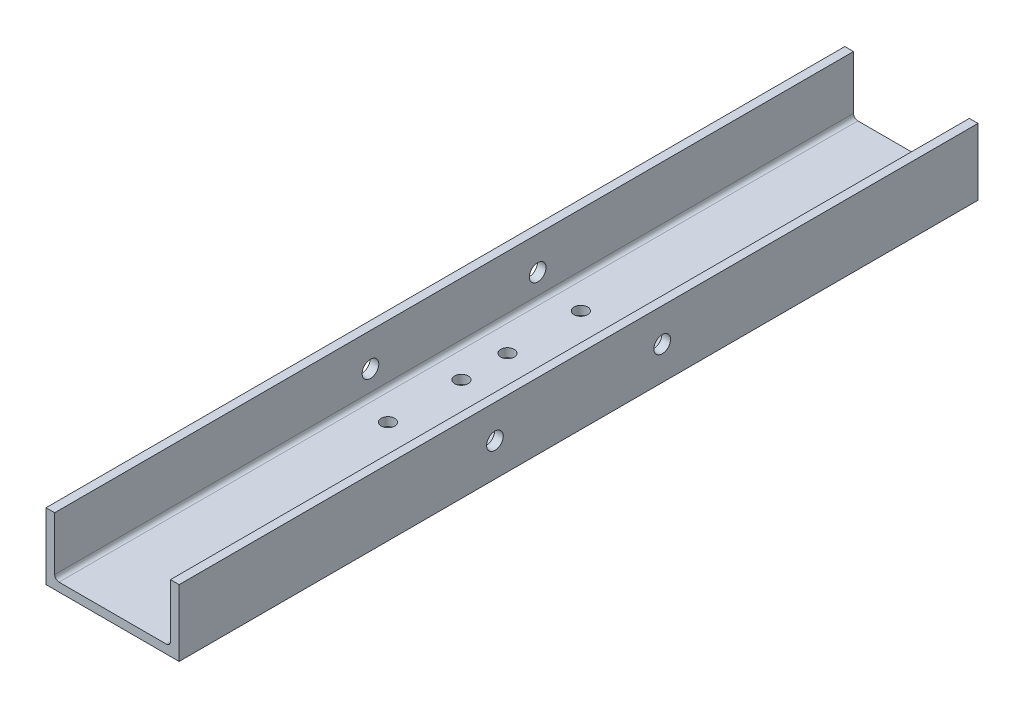
SolidWorks part; units mm, degrees
ref_plane "Front Plane" through (0, 0, 0) normal (0, 0, 1) x (1, 0, 0)
ref_plane "Top Plane" through (0, 0, 0) normal (0, 1, 0) x (1, 0, 0)
ref_plane "Right Plane" through (0, 0, 0) normal (1, 0, 0) x (0, 0, -1)
sketch "Sketch1" plane through (0, 0, 0) normal (0, 0, 1) x (1, 0, 0)
  line L0 (-25.4, 12.7) -> (-25.4, -12.7) construction
  line L1 (-25.4, -12.7) -> (25.4, -12.7) construction
  line L2 (25.4, -12.7) -> (25.4, 12.7) construction
  line L3 (22.098, -9.398) -> (-22.098, -9.398) construction
  line L4 (-22.098, -9.398) -> (-22.098, 12.7) construction
  line L6 (-22.098, 12.7) -> (-25.4, 12.7) construction
  line L7 (0, -12.7) -> (0, 0) construction
  line L8 (25.4, 12.7) -> (22.098, 12.7) construction
  line L9 (22.098, 12.7) -> (22.098, -9.398) construction
  line L10 (0, -9.398) -> (0, -12.7) construction
  point P4 (0, 0)
  point P11 (25.4, -9.398)
  dimension "Outside Height" = 25.4
  dimension "Outside Width" = 50.8
  dimension "Leg Thickness" = 3.302
  dimension "D1" = 12.7
  dimension "Inside Height" = 22.098
  dimension "Inside Width" = 44.196
  dimension "Base Thickness" = 3.302
sketch "Sketch2" plane through (0, 0, 0) normal (1, 0, 0) x (0, 0, -1)
  line L0 (210.695, 12.7) -> (-210.695, 12.7) construction
  line L1 (0, -9.398) -> (0, 12.7) construction
  point P0 (-159.895, 12.7)
  point P4 (0, 12.7)
  point P6 (159.895, 12.7)
  dimension "D1" = 50.8
  dimension "D2" = 50.8
  dimension "Length" = 421.39
sketch "Sketch3" plane through (0, 0, 0) normal (0, 0, 1) x (1, 0, 0)
  line L6 (-25.4, 12.7) -> (-25.4, -12.7)
  line L7 (-25.4, -12.7) -> (25.4, -12.7)
  line L8 (25.4, -12.7) -> (25.4, 12.7)
  line L9 (25.4, 12.7) -> (22.098, 12.7)
  line L10 (22.098, 12.7) -> (22.098, -9.398)
  line L11 (22.098, -9.398) -> (-22.098, -9.398)
  line L12 (-22.098, -9.398) -> (-22.098, 12.7)
  line L13 (-22.098, 12.7) -> (-25.4, 12.7)
extrude "Boss-Extrude1" add sketch "Sketch3" along normal mid plane 304.8
fillet "Fillet1" radius 1.651 2 edges at (22.098, -9.398, 0) (-22.098, -9.398, 0)
sketch "Sketch4" plane through (0, -9.398, 0) normal (0, 1, 0) x (1, 0, 0)
  line L0 (0, 152.4) -> (0, -152.4) construction
  line L1 (20.447, 152.4) -> (-20.447, 152.4) construction
  line L2 (20.447, -152.4) -> (-20.447, -152.4) construction
  line L3 (-23.5304, 0) -> (23.5304, 0) construction
  circle A0 centre (-10.5304, 8.79) radius 2.585
  circle A1 centre (10.4696, 8.79) radius 2.585
  circle A2 centre (-10.5304, 36.79) radius 2.585
  circle A3 centre (10.4696, 36.79) radius 2.585
  circle A4 centre (-10.5304, -36.79) radius 2.585
  circle A5 centre (10.4696, -36.79) radius 2.585
  circle A6 centre (10.4696, -8.79) radius 2.585
  circle A7 centre (-10.5304, -8.79) radius 2.585
  point P24 (0, 0)
  point P26 (0, 0)
  dimension "D1" = 5.17
  dimension "D2" = 5.17
  dimension "D3" = 28
  dimension "D4" = 8.79
  dimension "D5" = 8.79
  dimension "D6" = 28
extrude "Cut-Extrude1" cut sketch "Sketch4" against normal blind 10
sketch "Sketch5" plane through (0, -9.398, 0) normal (0, 1, 0) x (1, 0, 0)
  circle A0 centre (0, 62.5214) radius 3.18
  circle A2 centre (0, -62.52) radius 3.18
  circle A3 centre (-10.5304, -8.79) radius 2.585 construction
  dimension "D1" = 53.73
  dimension "D2" = 6.36
sketch "Sketch9" plane through (0, 0, 0) normal (1, 0, 0) x (0, 0, -1)
  line L0 (0, 0) -> (0, -12.7) construction
  line L1 (-152.4, -12.7) -> (152.4, -12.7) construction
  line L2 (0, 0) -> (-95.1707, 0) construction
  circle A0 centre (-31.91, 0) radius 3.18
  circle A1 centre (31.91, 0) radius 3.18
  dimension "D2" = 6.36
  dimension "D1" = 31.91
extrude "Cut-Extrude2" cut sketch "Sketch9" against normal mid plane 60
equation "\"D1@Boss-Extrude1\"=\"Length@Sketch2\""
equation "\"D2@Sketch2\"=\"D1@Sketch2\""
equation "\"D1@Sketch1\"=\"Outside Height@Sketch1\"/2"
equation "\"D1@Fillet1\"=\"Leg Thickness@Sketch1\"*.5"
equation "\"D1@Sketch2\"=\"Outside Width@Sketch1\"*1"
